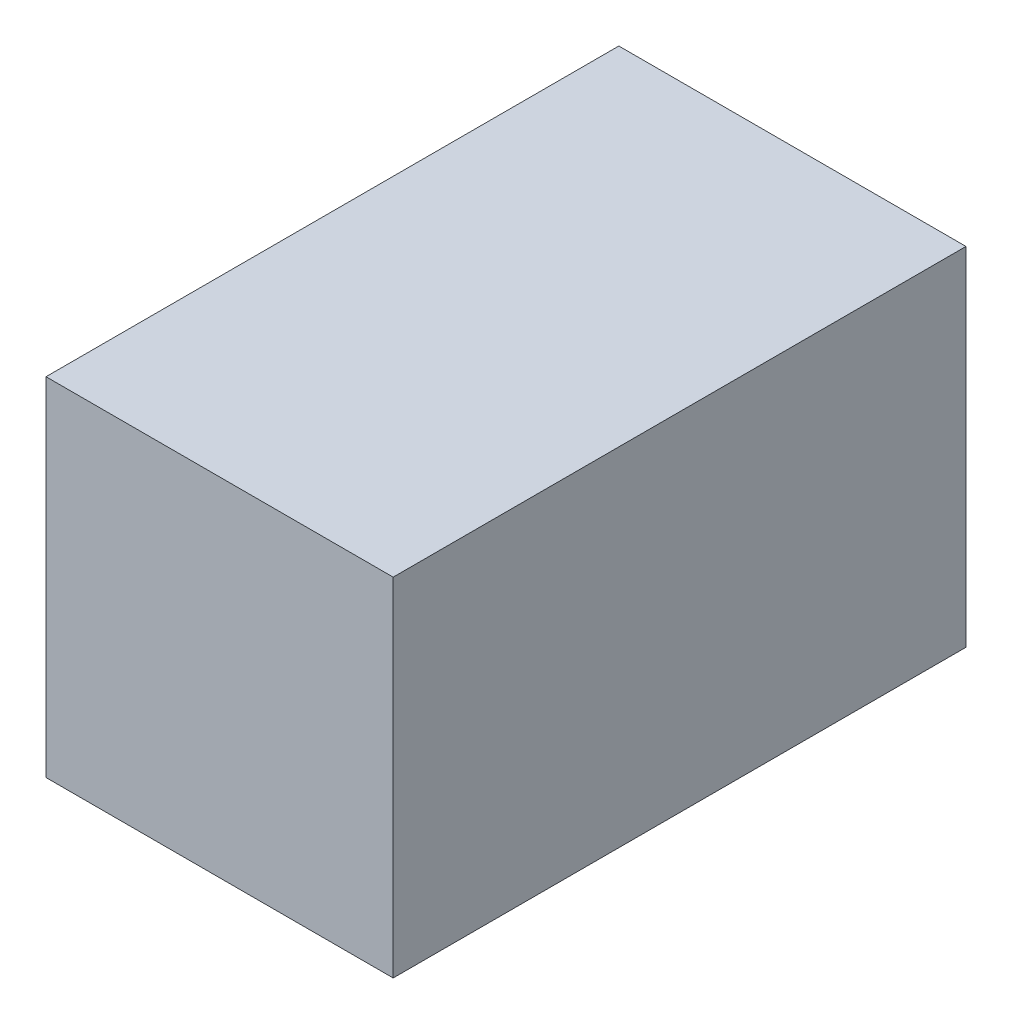
SolidWorks part; units mm, degrees
material "Plástico personalizado"
ref_plane "Alzado" through (0, 0, 0) normal (0, 0, 1) x (1, 0, 0)
ref_plane "Planta" through (0, 0, 0) normal (0, 1, 0) x (1, 0, 0)
ref_plane "Vista lateral" through (0, 0, 0) normal (1, 0, 0) x (0, 0, -1)
sketch "Croquis1" plane through (0, 0, 0) normal (0, 1, 0) x (1, 0, 0)
  line L1 (1, -1.65) -> (-1, -1.65)
  line L2 (1, -1.65) -> (1, 1.65)
  line L3 (1, 1.65) -> (-1, 1.65)
  line L4 (-1, -1.65) -> (-1, 1.65)
  line L5 (1, -1.65) -> (-1, 1.65) construction
  line L6 (1, 1.65) -> (-1, -1.65) construction
  point P0 (0, 0)
  dimension "D1" = 3.3
  dimension "D2" = 2
extrude "Saliente-Extruir1" add sketch "Croquis1" along normal blind 2
